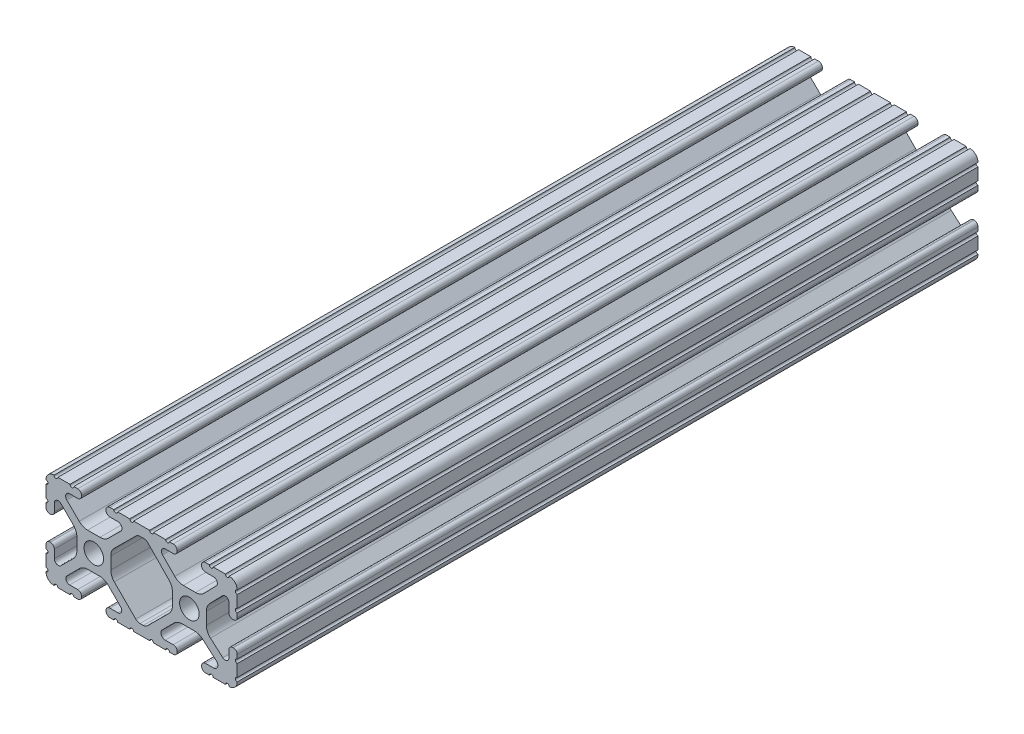
SolidWorks part; units mm, degrees
ref_plane "Front Plane" through (0, 0, 0) normal (0, 0, 1) x (1, 0, 0)
ref_plane "Top Plane" through (0, 0, 0) normal (0, 1, 0) x (1, 0, 0)
ref_plane "Right Plane" through (0, 0, 0) normal (1, 0, 0) x (0, 0, -1)
sketch "Sketch1" plane through (0, 0, 0) normal (0, 0, 1) x (1, 0, 0)
  line L0 (-7.2595, -3.8694) -> (-1.5457, -9.5728)
  line L1 (-8.1915, 1.6223) -> (-8.1915, -1.6223)
  line L2 (-1.504, 9.5765) -> (-7.252, 3.8768)
  line L3 (0.5515, 10.033) -> (-0.3952, 10.033)
  line L4 (7.2829, 3.8459) -> (1.6756, 9.5611)
  line L5 (8.1915, -1.6223) -> (8.1915, 1.6223)
  line L6 (1.5457, -9.5728) -> (7.2595, -3.8694)
  line L7 (-0.4332, -10.033) -> (0.4332, -10.033)
  line L8 (18.0171, 12.7) -> (16.9875, 12.7)
  line L9 (15.9385, 11.651) -> (15.9385, 11.5392)
  line L10 (16.9875, 10.4902) -> (19.1164, 10.4902)
  line L11 (19.8441, 8.7652) -> (16.619, 5.4551)
  line L12 (14.3449, 4.4958) -> (11.0833, 4.4958)
  line L13 (8.817, 5.4472) -> (5.5642, 8.7627)
  line L14 (6.2894, 10.4902) -> (8.4125, 10.4902)
  line L15 (9.4615, 11.5392) -> (9.4615, 11.651)
  line L16 (8.4125, 12.7) -> (7.3829, 12.7)
  line L17 (6.3669, 12.7) -> (3.1496, 12.7)
  line L18 (2.1336, 12.7) -> (-2.1336, 12.7)
  line L19 (-3.1496, 12.7) -> (-6.3669, 12.7)
  line L20 (-7.3829, 12.7) -> (-8.4125, 12.7)
  line L21 (-9.4615, 11.651) -> (-9.4615, 11.5392)
  line L22 (-8.4125, 10.4902) -> (-6.2836, 10.4902)
  line L23 (-5.5326, 8.6661) -> (-8.81, 5.4163)
  line L24 (-11.0455, 4.4958) -> (-14.3545, 4.4958)
  line L25 (-16.59, 5.4163) -> (-19.8674, 8.6661)
  line L26 (-19.1164, 10.4902) -> (-16.9875, 10.4902)
  line L27 (-15.9385, 11.5392) -> (-15.9385, 11.651)
  line L28 (-16.9875, 12.7) -> (-18.0171, 12.7)
  line L29 (-19.0331, 12.7) -> (-22.2504, 12.7)
  line L30 (-25.4, 9.5504) -> (-25.4, 6.3331)
  line L31 (-25.4, 5.3171) -> (-25.4, 4.2375)
  line L32 (-24.401, 3.2385) -> (-24.2392, 3.2385)
  line L33 (-23.1902, 4.2875) -> (-23.1902, 6.3347)
  line L34 (-21.434, 7.0665) -> (-18.148, 3.8082)
  line L35 (-17.2085, 1.5536) -> (-17.2085, -1.6952)
  line L36 (-18.1405, -3.9423) -> (-21.4316, -7.2274)
  line L37 (-23.1902, -6.498) -> (-23.1902, -4.2875)
  line L38 (-24.2392, -3.2385) -> (-24.351, -3.2385)
  line L39 (-25.4, -4.2875) -> (-25.4, -5.3171)
  line L40 (-25.4, -6.3331) -> (-25.4, -9.5504)
  line L41 (-22.2504, -12.7) -> (-19.0331, -12.7)
  line L42 (-18.0171, -12.7) -> (-16.9875, -12.7)
  line L43 (-15.9384, -11.651) -> (-15.9384, -11.5392)
  line L44 (-16.9875, -10.4902) -> (-19.1164, -10.4902)
  line L45 (-19.8341, -8.7551) -> (-16.4966, -5.4237)
  line L46 (-14.2536, -4.4958) -> (-11.1464, -4.4958)
  line L47 (-8.9034, -5.4237) -> (-5.5659, -8.7551)
  line L48 (-6.2836, -10.4902) -> (-8.4125, -10.4902)
  line L49 (-9.4616, -11.5392) -> (-9.4616, -11.651)
  line L50 (-8.4125, -12.7) -> (-7.3829, -12.7)
  line L51 (-6.3669, -12.7) -> (-3.1496, -12.7)
  line L52 (-2.1336, -12.7) -> (2.1336, -12.7)
  line L53 (3.1496, -12.7) -> (6.3669, -12.7)
  line L54 (7.3829, -12.7) -> (8.4125, -12.7)
  line L55 (9.4616, -11.651) -> (9.4616, -11.5392)
  line L56 (8.4125, -10.4902) -> (6.2894, -10.4902)
  line L57 (5.4807, -8.5353) -> (8.5979, -5.4237)
  line L58 (10.8409, -4.4958) -> (14.1026, -4.4958)
  line L59 (16.1879, -5.2766) -> (19.8682, -8.4822)
  line L60 (19.1164, -10.4902) -> (16.9875, -10.4902)
  line L61 (15.9384, -11.5392) -> (15.9384, -11.651)
  line L62 (16.9875, -12.7) -> (18.0171, -12.7)
  line L63 (19.0331, -12.7) -> (22.2504, -12.7)
  line L64 (25.4, -9.5504) -> (25.4, -6.3331)
  line L65 (25.4, -5.3171) -> (25.4, -4.2375)
  line L66 (24.401, -3.2385) -> (24.1892, -3.2385)
  line L67 (23.1902, -4.2375) -> (23.1902, -6.1559)
  line L68 (21.584, -6.8869) -> (18.2982, -4.025)
  line L69 (17.2085, -1.6308) -> (17.2085, 1.6308)
  line L70 (18.1094, 3.8465) -> (21.5263, 7.3534)
  line L71 (23.1902, 6.6769) -> (23.1902, 4.2375)
  line L72 (24.1892, 3.2385) -> (24.401, 3.2385)
  line L73 (25.4, 4.2375) -> (25.4, 5.3171)
  line L74 (25.4, 6.3332) -> (25.4, 9.5504)
  line L75 (22.2504, 12.7) -> (19.0331, 12.7)
  circle A0 centre (-12.7, 0) radius 2.6035
  circle A1 centre (12.7, 0) radius 2.6035
  arc A2 (-1.5457, -9.5728) -> (-0.4332, -10.033) centre (-0.4332, -8.4582) ccw
  arc A3 (-8.1915, -1.6223) -> (-7.2595, -3.8694) centre (-5.0165, -1.6223) ccw
  arc A4 (-7.252, 3.8768) -> (-8.1915, 1.6223) centre (-5.0165, 1.6223) ccw
  arc A5 (-0.3952, 10.033) -> (-1.504, 9.5765) centre (-0.3952, 8.4582) ccw
  arc A6 (1.6756, 9.5611) -> (0.5515, 10.033) centre (0.5515, 8.4582) ccw
  arc A7 (8.1915, 1.6223) -> (7.2829, 3.8459) centre (5.0165, 1.6223) ccw
  arc A8 (7.2595, -3.8694) -> (8.1915, -1.6223) centre (5.0165, -1.6223) ccw
  arc A9 (0.4332, -10.033) -> (1.5457, -9.5728) centre (0.4332, -8.4582) ccw
  arc A10 (18.0171, 12.7) -> (19.0331, 12.7) centre (18.5251, 12.7) ccw
  arc A11 (16.9875, 12.7) -> (15.9385, 11.651) centre (16.9875, 11.651) ccw
  arc A12 (15.9385, 11.5392) -> (16.9875, 10.4902) centre (16.9875, 11.5392) ccw
  arc A13 (19.8441, 8.7652) -> (19.1164, 10.4902) centre (19.1164, 9.4742) ccw
  arc A14 (14.3449, 4.4958) -> (16.619, 5.4551) centre (14.3449, 7.6708) ccw
  arc A15 (8.817, 5.4472) -> (11.0833, 4.4958) centre (11.0833, 7.6708) ccw
  arc A16 (6.2894, 10.4902) -> (5.5642, 8.7627) centre (6.2894, 9.4742) ccw
  arc A17 (8.4125, 10.4902) -> (9.4615, 11.5392) centre (8.4125, 11.5392) ccw
  arc A18 (9.4615, 11.651) -> (8.4125, 12.7) centre (8.4125, 11.651) ccw
  arc A19 (6.3669, 12.7) -> (7.3829, 12.7) centre (6.8749, 12.7) ccw
  arc A20 (2.1336, 12.7) -> (3.1496, 12.7) centre (2.6416, 12.7) ccw
  arc A21 (-3.1496, 12.7) -> (-2.1336, 12.7) centre (-2.6416, 12.7) ccw
  arc A22 (-7.3829, 12.7) -> (-6.3669, 12.7) centre (-6.8749, 12.7) ccw
  arc A23 (-8.4125, 12.7) -> (-9.4615, 11.651) centre (-8.4125, 11.651) ccw
  arc A24 (-9.4615, 11.5392) -> (-8.4125, 10.4902) centre (-8.4125, 11.5392) ccw
  arc A25 (-5.5326, 8.6661) -> (-6.2836, 10.4902) centre (-6.2836, 9.4235) ccw
  arc A26 (-11.0455, 4.4958) -> (-8.81, 5.4163) centre (-11.0455, 7.6708) ccw
  arc A27 (-16.59, 5.4163) -> (-14.3545, 4.4958) centre (-14.3545, 7.6708) ccw
  arc A28 (-19.1164, 10.4902) -> (-19.8674, 8.6661) centre (-19.1164, 9.4235) ccw
  arc A29 (-16.9875, 10.4902) -> (-15.9385, 11.5392) centre (-16.9875, 11.5392) ccw
  arc A30 (-15.9385, 11.651) -> (-16.9875, 12.7) centre (-16.9875, 11.651) ccw
  arc A31 (-19.0331, 12.7) -> (-18.0171, 12.7) centre (-18.5251, 12.7) ccw
  arc A32 (-23.2664, 12.6998) -> (-22.2504, 12.7) centre (-22.7584, 12.7) ccw
  arc A33 (-23.2664, 12.6998) -> (-25.3998, 10.5664) centre (-23.2918, 10.5918) ccw
  arc A34 (-25.4, 9.5504) -> (-25.3998, 10.5664) centre (-25.4, 10.0584) ccw
  arc A35 (-25.4, 5.3171) -> (-25.4, 6.3331) centre (-25.4, 5.8251) ccw
  arc A36 (-25.4, 4.2375) -> (-24.401, 3.2385) centre (-24.401, 4.2375) ccw
  arc A37 (-24.2392, 3.2385) -> (-23.1902, 4.2875) centre (-24.2392, 4.2875) ccw
  arc A38 (-21.434, 7.0665) -> (-23.1902, 6.3347) centre (-22.1596, 6.3347) ccw
  arc A39 (-17.2085, 1.5536) -> (-18.148, 3.8082) centre (-20.3835, 1.5536) ccw
  arc A40 (-18.1405, -3.9423) -> (-17.2085, -1.6952) centre (-20.3835, -1.6952) ccw
  arc A41 (-23.1902, -6.498) -> (-21.4316, -7.2274) centre (-22.1596, -6.498) ccw
  arc A42 (-23.1902, -4.2875) -> (-24.2392, -3.2385) centre (-24.2392, -4.2875) ccw
  arc A43 (-24.351, -3.2385) -> (-25.4, -4.2875) centre (-24.351, -4.2875) ccw
  arc A44 (-25.4, -6.3331) -> (-25.4, -5.3171) centre (-25.4, -5.8251) ccw
  arc A45 (-25.3998, -10.5664) -> (-25.4, -9.5504) centre (-25.4, -10.0584) ccw
  arc A46 (-25.3998, -10.5664) -> (-23.2664, -12.6998) centre (-23.2918, -10.5918) ccw
  arc A47 (-22.2504, -12.7) -> (-23.2664, -12.6998) centre (-22.7584, -12.7) ccw
  arc A48 (-18.0171, -12.7) -> (-19.0331, -12.7) centre (-18.5251, -12.7) ccw
  arc A49 (-16.9875, -12.7) -> (-15.9384, -11.651) centre (-16.9875, -11.651) ccw
  arc A50 (-15.9384, -11.5392) -> (-16.9875, -10.4902) centre (-16.9875, -11.5392) ccw
  arc A51 (-19.8341, -8.7551) -> (-19.1164, -10.4902) centre (-19.1164, -9.4742) ccw
  arc A52 (-14.2536, -4.4958) -> (-16.4966, -5.4237) centre (-14.2536, -7.6708) ccw
  arc A53 (-8.9034, -5.4237) -> (-11.1464, -4.4958) centre (-11.1464, -7.6708) ccw
  arc A54 (-6.2836, -10.4902) -> (-5.5659, -8.7551) centre (-6.2836, -9.4742) ccw
  arc A55 (-8.4125, -10.4902) -> (-9.4616, -11.5392) centre (-8.4125, -11.5392) ccw
  arc A56 (-9.4616, -11.651) -> (-8.4125, -12.7) centre (-8.4125, -11.651) ccw
  arc A57 (-6.3669, -12.7) -> (-7.3829, -12.7) centre (-6.8749, -12.7) ccw
  arc A58 (-2.1336, -12.7) -> (-3.1496, -12.7) centre (-2.6416, -12.7) ccw
  arc A59 (3.1496, -12.7) -> (2.1336, -12.7) centre (2.6416, -12.7) ccw
  arc A60 (7.3829, -12.7) -> (6.3669, -12.7) centre (6.8749, -12.7) ccw
  arc A61 (8.4125, -12.7) -> (9.4616, -11.651) centre (8.4125, -11.651) ccw
  arc A62 (9.4616, -11.5392) -> (8.4125, -10.4902) centre (8.4125, -11.5392) ccw
  arc A63 (5.4807, -8.5353) -> (6.2894, -10.4902) centre (6.2894, -9.3455) ccw
  arc A64 (10.8409, -4.4958) -> (8.5979, -5.4237) centre (10.8409, -7.6708) ccw
  arc A65 (16.1879, -5.2766) -> (14.1026, -4.4958) centre (14.1026, -7.6708) ccw
  arc A66 (19.1164, -10.4902) -> (19.8682, -8.4822) centre (19.1164, -9.3455) ccw
  arc A67 (16.9875, -10.4902) -> (15.9384, -11.5392) centre (16.9875, -11.5392) ccw
  arc A68 (15.9384, -11.651) -> (16.9875, -12.7) centre (16.9875, -11.651) ccw
  arc A69 (19.0331, -12.7) -> (18.0171, -12.7) centre (18.5251, -12.7) ccw
  arc A70 (23.2664, -12.6998) -> (22.2504, -12.7) centre (22.7584, -12.7) ccw
  arc A71 (23.2664, -12.6998) -> (25.3998, -10.5664) centre (23.2918, -10.5918) ccw
  arc A72 (25.4, -9.5504) -> (25.3998, -10.5664) centre (25.4, -10.0584) ccw
  arc A73 (25.4, -5.3171) -> (25.4, -6.3331) centre (25.4, -5.8251) ccw
  arc A74 (25.4, -4.2375) -> (24.401, -3.2385) centre (24.401, -4.2375) ccw
  arc A75 (24.1892, -3.2385) -> (23.1902, -4.2375) centre (24.1892, -4.2375) ccw
  arc A76 (21.584, -6.8869) -> (23.1902, -6.1559) centre (22.2207, -6.1559) ccw
  arc A77 (17.2085, -1.6308) -> (18.2982, -4.025) centre (20.3835, -1.6308) ccw
  arc A78 (18.1094, 3.8465) -> (17.2085, 1.6308) centre (20.3835, 1.6308) ccw
  arc A79 (23.1902, 6.6769) -> (21.5263, 7.3534) centre (22.2207, 6.6769) ccw
  arc A80 (23.1902, 4.2375) -> (24.1892, 3.2385) centre (24.1892, 4.2375) ccw
  arc A81 (24.401, 3.2385) -> (25.4, 4.2375) centre (24.401, 4.2375) ccw
  arc A82 (25.4, 6.3332) -> (25.4, 5.3171) centre (25.4, 5.8251) ccw
  arc A83 (25.3998, 10.5664) -> (25.4, 9.5504) centre (25.4, 10.0584) ccw
  arc A84 (25.3998, 10.5664) -> (23.2664, 12.6998) centre (23.2918, 10.5918) ccw
  arc A85 (22.2504, 12.7) -> (23.2664, 12.6998) centre (22.7584, 12.7) ccw
  point P248 (0, 10.033)
extrude "Boss-Extrude1" add sketch "Sketch1" along normal mid plane 196.85
